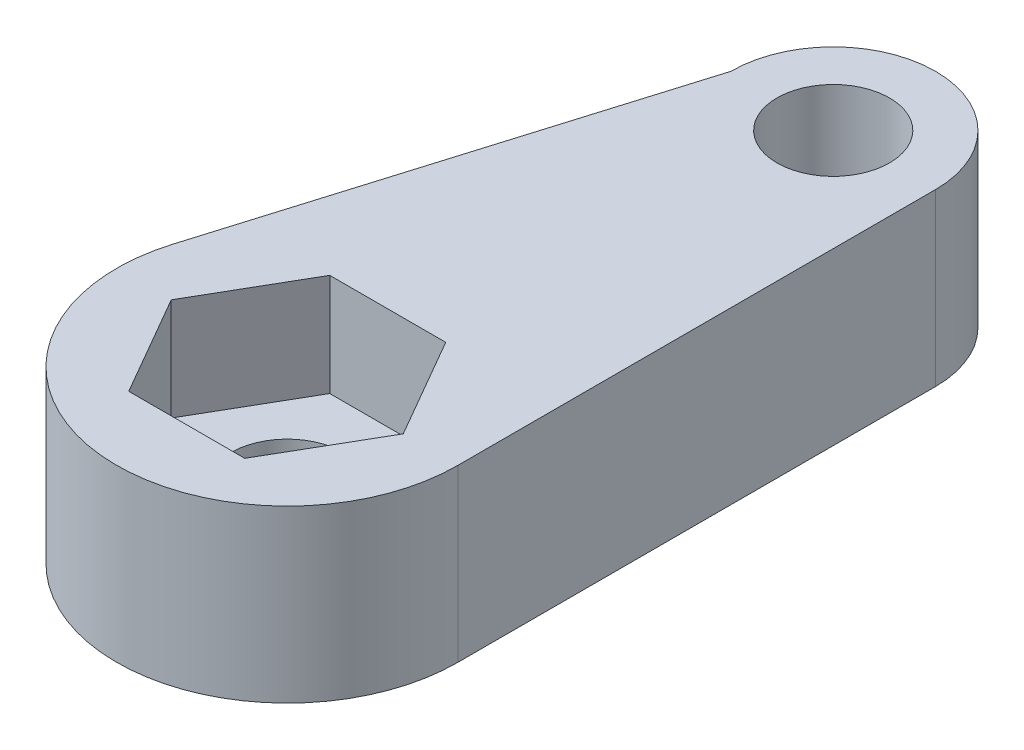
SolidWorks part; units mm, degrees
ref_plane "Front Plane" through (0, 0, 0) normal (0, 0, 1) x (1, 0, 0)
ref_plane "Top Plane" through (0, 0, 0) normal (0, 1, 0) x (1, 0, 0)
ref_plane "Right Plane" through (0, 0, 0) normal (1, 0, 0) x (0, 0, -1)
sketch "Sketch1" plane through (0, 0, 0) normal (0, 1, 0) x (1, 0, 0)
  line L0 (3.2761, -6.3528) -> (1.5761, -3.4083) construction
  line L1 (1.5761, -3.4083) -> (-1.8239, -3.4083) construction
  line L2 (-1.8239, -3.4083) -> (-3.5239, -6.3528) construction
  line L3 (-3.5239, -6.3528) -> (-1.8239, -9.2972) construction
  line L4 (-1.8239, -9.2972) -> (1.5761, -9.2972) construction
  line L5 (1.5761, -9.2972) -> (3.2761, -6.3528) construction
  line L6 (-1.1239, 7.6472) -> (-4.9109, -4.9081)
  line L7 (4.8761, 7.6472) -> (4.8761, -6.352)
  circle A0 centre (1.8761, 7.6472) radius 1.65
  circle A1 centre (-0.1239, -6.352) radius 1.65
  arc A3 (-4.9109, -4.9081) -> (4.8761, -6.352) centre (-0.1239, -6.352) ccw
  arc A4 (4.8761, 7.6472) -> (-1.1239, 7.6472) centre (1.8761, 7.6472) ccw
  dimension "D2" = 10
  dimension "D3" = 6
  dimension "D1" = 6.8
extrude "Boss-Extrude1" add sketch "Sketch1" along normal blind 5
sketch "Sketch2" plane through (0, 5, 0) normal (0, 1, 0) x (1, 0, 0)
  line L1 (3.2761, -6.3528) -> (1.5768, -3.4079)
  line L2 (1.5768, -3.4079) -> (-1.8232, -3.4071)
  line L3 (-1.8232, -3.4071) -> (-3.5239, -6.3511)
  line L4 (-3.5239, -6.3511) -> (-1.8246, -9.296)
  line L5 (-1.8246, -9.296) -> (1.5754, -9.2968)
  line L6 (1.5754, -9.2968) -> (3.2761, -6.3528)
  circle A0 centre (-0.1239, -6.352) radius 2.9445 construction
extrude "Cut-Extrude1" cut sketch "Sketch2" against normal blind 3
